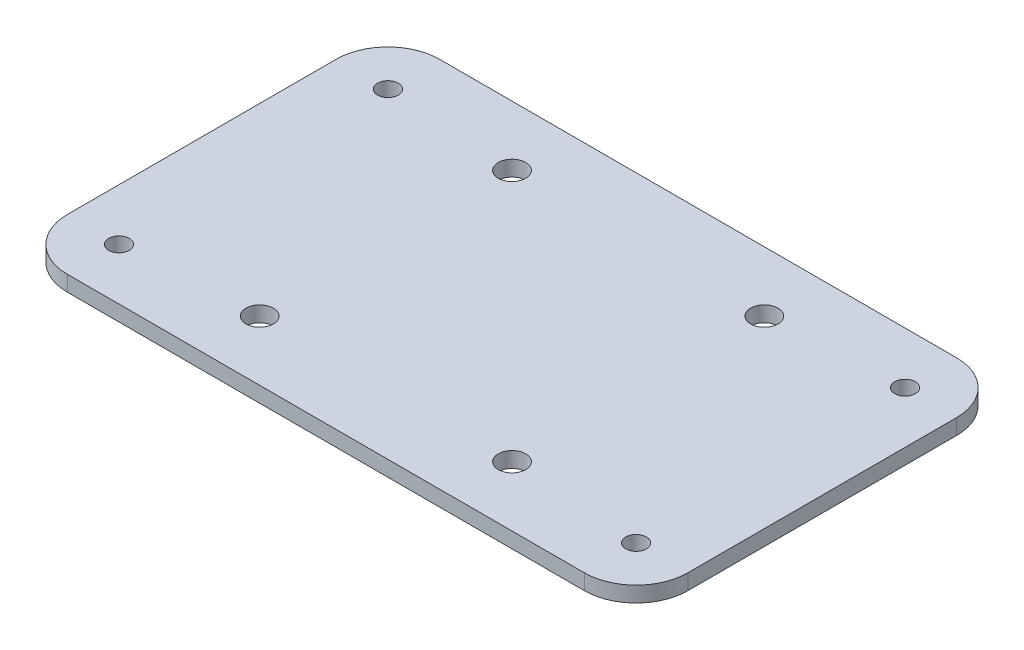
SolidWorks part; units mm, degrees
ref_plane "前视基准面" through (0, 0, 0) normal (0, 0, 1) x (1, 0, 0)
ref_plane "上视基准面" through (0, 0, 0) normal (0, 1, 0) x (1, 0, 0)
ref_plane "右视基准面" through (0, 0, 0) normal (1, 0, 0) x (0, 0, -1)
other "Configuration Table"
sketch "草图1" plane through (0, 0, 0) normal (0, 1, 0) x (1, 0, 0)
  line L0 (-24.3952, 24.3952) -> (0, 0) construction
  line L1 (-60, -36) -> (60, -36)
  line L2 (-60, -36) -> (-60, 36)
  line L3 (-60, 36) -> (60, 36)
  line L4 (60, -36) -> (60, 36)
  line L5 (-60, -36) -> (60, 36) construction
  line L6 (-60, 36) -> (60, -36) construction
  line L7 (0, -1000) -> (0, 49000) construction
  circle A0 centre (-24.3952, 24.3952) radius 2.65
  circle A1 centre (24.3952, 24.3952) radius 2.65
  circle A2 centre (24.3952, -24.3952) radius 2.65
  circle A3 centre (-24.3952, -24.3952) radius 2.65
  circle A4 centre (-50, 26) radius 2
  circle A5 centre (-50, -26) radius 2
  circle A6 centre (50, -26) radius 2
  circle A7 centre (50, 26) radius 2
  point P0 (0, 0)
  point P18 (0, 0)
  dimension "D1" = 34.5
  dimension "D6" = 4
  dimension "D7" = 4
  dimension "D8" = 5.3
  dimension "D9" = 10
  dimension "D10" = 10
  dimension "D11" = 10
  dimension "D12" = 10
  dimension "D2" = 45
  dimension "D4" = 72
  dimension "D5" = 120
  dimension "D3" = 4
extrude "凸台-拉伸1" add sketch "草图1" along normal blind 3
fillet "圆角1" radius 10 4 edges at (-60, 1.5, 36) (60, 1.5, 36) (60, 1.5, -36) (-60, 1.5, -36)
